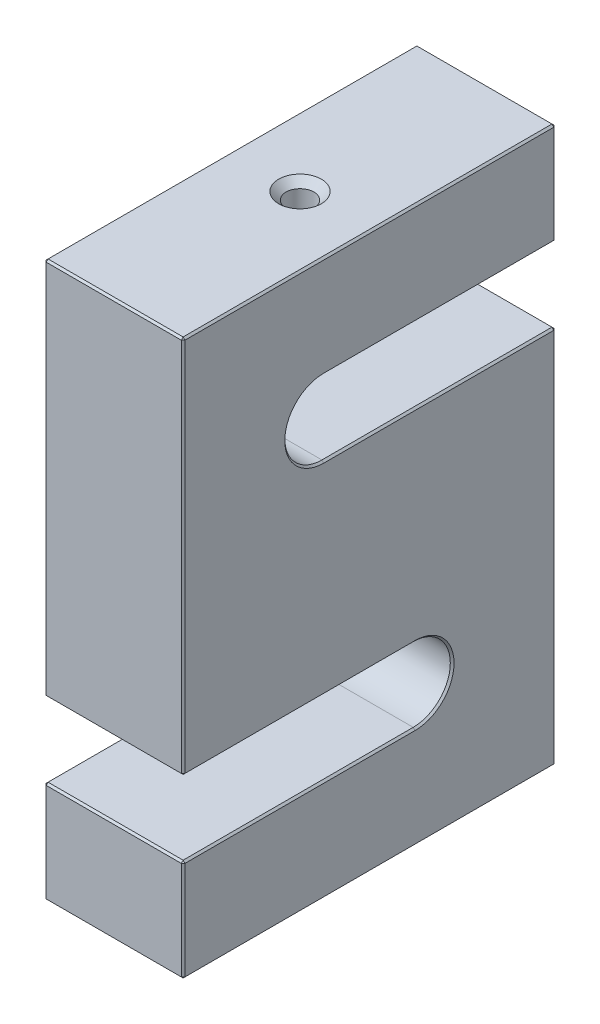
SolidWorks part; units mm, degrees
ref_plane "Front" through (0, 0, 0) normal (0, 0, 1) x (1, 0, 0)
ref_plane "Top" through (0, 0, 0) normal (0, 1, 0) x (1, 0, 0)
ref_plane "Right" through (0, 0, 0) normal (1, 0, 0) x (0, 0, -1)
sketch "Sketch1" plane through (0, 0, 0) normal (1, 0, 0) x (0, 0, -1)
  line L0 (-25.5, 0) -> (25.5, 0) construction
  line L1 (25.5, -38) -> (-25.5, -38) construction
  line L2 (25.5, -38) -> (25.5, 13.92)
  line L3 (25.5, 38) -> (-25.5, 38) construction
  line L4 (-25.5, -38) -> (-25.5, 38) construction
  line L5 (25.5, -38) -> (-25.5, 38) construction
  line L6 (25.5, 38) -> (-25.5, -38) construction
  line L7 (-25.5, 19) -> (25.5, 19) construction
  line L8 (-6.25, 19) -> (29.6244, 19) construction
  line L9 (-6.25, 24.08) -> (25.5, 24.08) construction
  line L10 (-6.25, 13.92) -> (25.5, 13.92) construction
  line L11 (6.25, -24.03) -> (-25.5, -24.03)
  line L12 (6.25, -13.87) -> (-25.5, -13.87) construction
  line L13 (11.33, -18.95) -> (-25.5, -18.95) construction
  line L14 (25.5, 38) -> (25.5, 24.08)
  line L15 (25.5, 24.08) -> (-6.25, 24.08)
  line L16 (25.5, 38) -> (-25.5, 38)
  line L17 (-25.5, 38) -> (-25.5, -13.87)
  line L18 (6.25, -13.87) -> (-25.5, -13.87)
  line L19 (25.5, 24.08) -> (25.5, 38)
  line L20 (-25.5, -24.03) -> (-25.5, -38)
  line L21 (-25.5, -38) -> (25.5, -38)
  line L23 (25.5, 13.92) -> (-6.25, 13.92)
  arc A0 (-6.25, 24.08) -> (-6.25, 13.92) centre (-6.25, 19) ccw construction
  arc A2 (6.25, -24.03) -> (6.25, -13.87) centre (6.25, -18.95) ccw construction
  arc A3 (-6.25, 24.08) -> (-6.25, 13.92) centre (-6.25, 19) ccw
  arc A4 (6.25, -13.87) -> (6.25, -24.03) centre (6.25, -18.95) cw
  point P0 (0, 0)
  point P12 (8.4372, 19)
  point P24 (0, 0.025)
  dimension "D1" = 51
  dimension "D2" = 76
  dimension "D3" = 19
  dimension "D6" = 10.16
  dimension "D7" = 19.05
  dimension "D5" = 2
extrude "Boss-Extrude1" add sketch "Sketch1" along normal blind 19 contours L18 A4 L11 L20 L21 L2 L23 A3 L15 L14 L16 L17
sketch "Sketch2" plane through (0, -38, 0) normal (0, -1, 0) x (1, 0, 0)
  line L0 (9.5, 25.5) -> (9.5, -25.5) construction
  line L1 (19, 25.5) -> (0, 25.5) construction
  line L2 (19, -25.5) -> (0, -25.5) construction
  line L3 (0, 0) -> (19, 0) construction
  line L4 (0, 25.5) -> (0, -25.5) construction
  line L5 (19, 25.5) -> (19, -25.5) construction
  circle A2 centre (9.5, 0) radius 1.905
  dimension "D1" = 3.81
extrude "Cut-Extrude1" cut sketch "Sketch2" against normal blind 10.16
chamfer "Chamfer1" distance 1.016 angle 45 1 edges at (9.5, -38, -1.905)
chamfer "Chamfer2" distance 0.254 angle 45 32 edges at (0, -38, 0) (0, 24.08, -9.625) (0, 38, 0) (0, -24.03, 9.625) (0, -18.95, -11.33) (0, -13.87, 9.625) (0, 19, 11.33) (0, 13.92, -9.625) (9.5, 24.08, -25.5) (0, 31.04, -25.5) (9.5, 38, -25.5) (9.5, -38, -25.5) (0, -12.04, -25.5) (9.5, 13.92, -25.5) (9.5, -24.03, 25.5) (0, -31.015, 25.5) (9.5, -38, 25.5) (9.5, 38, 25.5) (0, 12.065, 25.5) (9.5, -13.87, 25.5) (19, 12.065, 25.5) (19, 38, 0) (19, 31.04, -25.5) (19, 24.08, -9.625) (19, 19, 11.33) (19, 13.92, -9.625) (19, -12.04, -25.5) (19, -38, 0) (19, -31.015, 25.5) (19, -24.03, 9.625) (19, -18.95, -11.33) (19, -13.87, 9.625)
mirror "Mirror3" about plane through (0, 0, 0) normal (0, 1, 0) of "Cut-Extrude1"
chamfer "Chamfer3" distance 1.016 angle 45 1 edges at (9.5, 38, -1.905)
